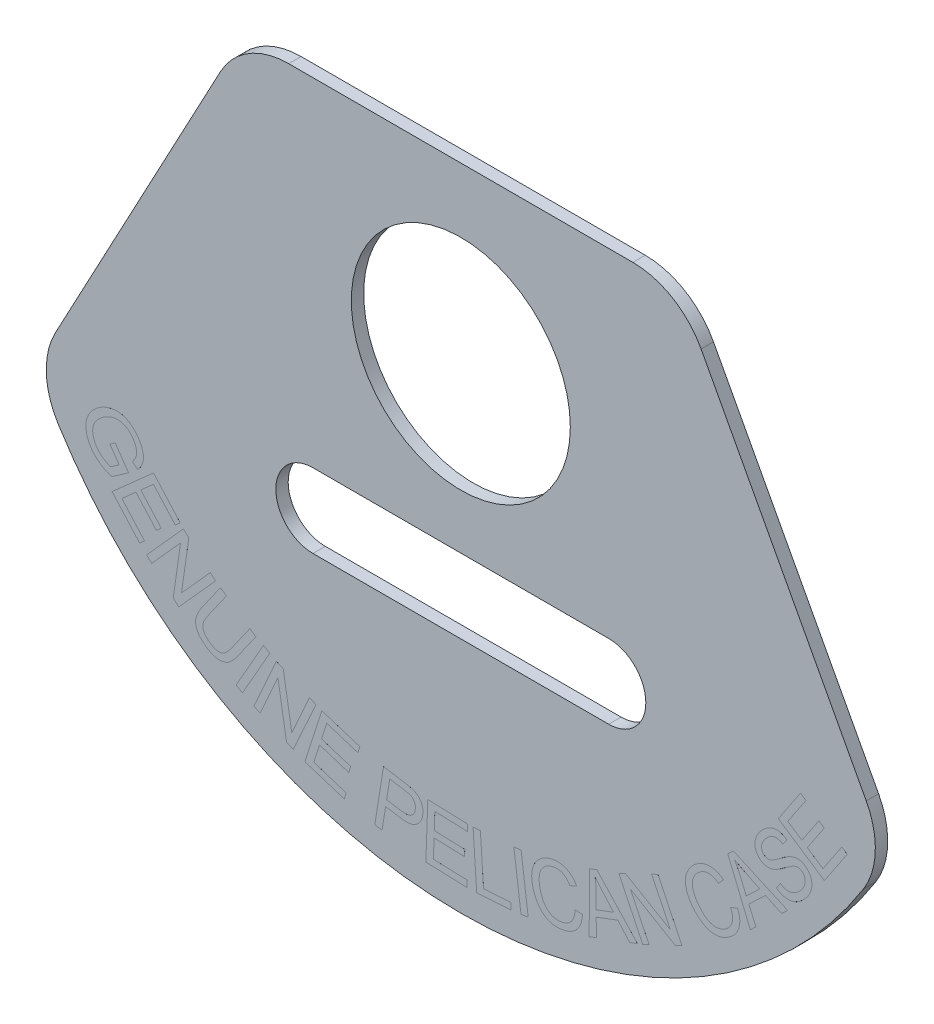
SolidWorks part; units mm, degrees
material "Nylon 6/10"
ref_plane "Front" through (0, 0, 0) normal (0, 0, 1) x (1, 0, 0)
ref_plane "Top" through (0, 0, 0) normal (0, 1, 0) x (1, 0, 0)
ref_plane "Right" through (0, 0, 0) normal (1, 0, 0) x (0, 0, -1)
sketch "Sketch1" plane through (0, 0, 0) normal (0, 0, 1) x (1, 0, 0)
  line L0 (-8.9662, 7.1374) -> (8.9662, 7.1374)
  line L1 (8.9662, 7.1374) -> (17.4625, -8.7512)
  line L2 (-8.9662, 7.1374) -> (-17.4625, -8.7512)
  line L3 (-6.0706, -8.255) -> (6.0706, -8.255) construction
  line L4 (-6.0706, -9.779) -> (6.0706, -9.779)
  line L5 (-6.0706, -6.731) -> (6.0706, -6.731)
  arc A0 (-17.4625, -8.7512) -> (17.4625, -8.7512) centre (0, 0) ccw
  circle A1 centre (0, 0) radius 4.4958
  arc A2 (-6.0706, -9.779) -> (-6.0706, -6.731) centre (-6.0706, -8.255) cw
  arc A3 (6.0706, -9.779) -> (6.0706, -6.731) centre (6.0706, -8.255) ccw
  point P11 (0, -8.255)
  dimension "D1" = 8.9916
  dimension "D3" = 2.6416
  dimension "D5" = 26.67
  dimension "D6" = 8.255
  dimension "D2" = 17.9324
  dimension "D4" = 34.925
  dimension "D7" = 12.1412
  dimension "D8" = 1.524
  dimension "D9" = 1.524
extrude "Extrude1" add sketch "Sketch1" along normal blind 0.508
fillet "Fillet1" radius 3.175 4 edges at (-8.9662, 7.1374, 0.254) (-17.4625, -8.7512, 0.254) (17.4625, -8.7512, 0.254) (8.9662, 7.1374, 0.254)
sketch "Sketch2" plane through (0, 0, 0.508) normal (0, 0, 1) x (1, 0, 0)
  arc A0 (-15.8817, -9.4904) -> (15.8817, -9.4904) centre (0, 0) ccw construction
  text T0 "GENUINE PELICAN CASE" font "Arial" height 2.286
extrude "Extrude2" add sketch "Sketch2" along normal blind 0.0001
